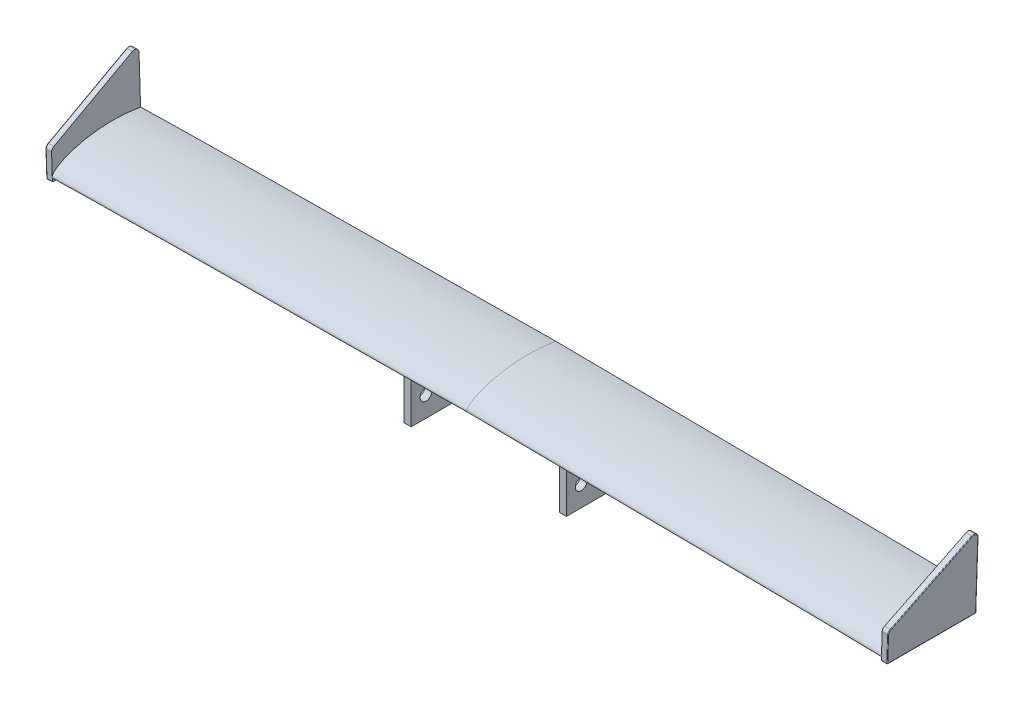
SolidWorks part; units mm, degrees
ref_plane "Front Plane" through (0, 0, 0) normal (0, 0, 1) x (1, 0, 0)
ref_plane "Top Plane" through (0, 0, 0) normal (0, 1, 0) x (1, 0, 0)
ref_plane "Right Plane" through (0, 0, 0) normal (1, 0, 0) x (0, 0, -1)
sketch "Sketch1" plane through (0, 0, 0) normal (1, 0, 0) x (0, 0, -1)
  spline S0 degree 3 poles (0, 0) (-7.6862, 24.2275) (121.2922, 86.4859) (300, 56.4342) knots 0 0 0 0 1 1 1 1
  spline S1 degree 2 poles (0, 0) (64.6593, -8.9294) (300, 56.4342) knots 0 0 0 1 1 1
  dimension "D1" = 300
sketch "Sketch2" plane through (0, 0, 0) normal (0, 0, 1) x (1, 0, 0)
  spline S0 degree 2 poles (0, 0) (1291.911, -11.5274) (1399.8962, -16.1505) knots 0 0 0 1 1 1
  dimension "D1" = 1400
sweep "Sweep1" add profiles "Sketch1" path "Sketch2"
sketch "Sketch7" plane through (1398.838, -47.3877, 0) normal (0.9994, -0.0339, 0) x (0, 0, -1)
  line L4 (0, 18.955) -> (0, 114.1571)
  line L5 (0, 114.1571) -> (300, 269.9514)
  line L6 (300, 269.9514) -> (300, 18.955)
  line L7 (300, 18.955) -> (0, 18.955)
  dimension "D1" = 250.9964
extrude "Boss-Extrude1" add sketch "Sketch7" along normal blind 20
fillet "Fillet1" radius 15 2 edges at (1417.972, 222.0704, -300) (1412.6973, 66.3654, 0)
fillet "Fillet2" radius 2 8 edges at (1420.9257, 13.8995, 0) (1422.6467, 64.7032, -2.1802) (1425.2074, 140.2913, -143.0869) (1427.5643, 209.8667, -292.7879) (1419.4683, -29.1207, -150) (1423.2993, 83.9668, -300) (1409.474, -28.7821, -300) (1409.474, -28.7821, 0)
sketch "Sketch8" plane through (0, 0, 0) normal (0, 1, 0) x (1, 0, 0)
  line L0 (0, 300) -> (0, 0) construction
  line L1 (250, 62) -> (274, 62)
  line L2 (250, 62) -> (250, 242)
  line L3 (250, 242) -> (274, 242)
  line L4 (274, 62) -> (274, 242)
  line L5 (0, 0) -> (1399.8962, 0) construction
  dimension "D1" = 250
  dimension "D2" = 180
  dimension "D3" = 24
  dimension "D4" = 62
extrude "Boss-Extrude2" add sketch "Sketch8" along normal up to next and the other way blind 200
sketch "Sketch9" plane through (274, 0, 0) normal (1, 0, 0) x (0, 0, -1)
  line L0 (242, -200) -> (242, 38.2843) construction
  line L1 (62, -200) -> (242, -200) construction
  circle A0 centre (202, -40) radius 20
  dimension "D1" = 40
  dimension "D2" = 40
  dimension "D3" = 160
extrude "Cut-Extrude1" cut sketch "Sketch9" against normal up to next
pattern_linear "LPattern1" count 2 spacing 90 along (0, -1, 0) count 2 spacing 90 along (0, 0, 1) of "Cut-Extrude1"
mirror "Mirror1" about plane through (0, 0, 0) normal (1, 0, 0) of "Sweep1", "Boss-Extrude1", "Fillet1", "Fillet2", "Boss-Extrude2", "Cut-Extrude1", "LPattern1"
